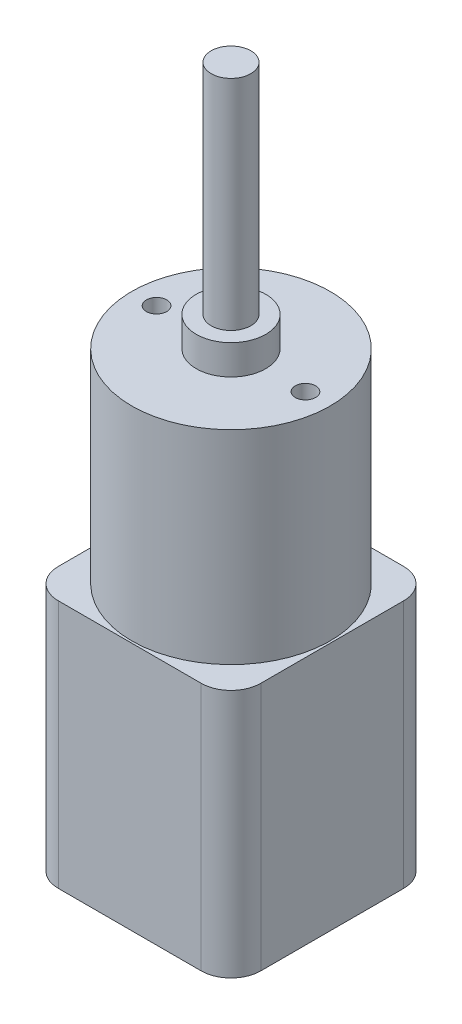
SolidWorks part; units mm, degrees
ref_plane "Front Plane" through (0, 0, 0) normal (0, 0, 1) x (1, 0, 0)
ref_plane "Top Plane" through (0, 0, 0) normal (0, 1, 0) x (1, 0, 0)
ref_plane "Right Plane" through (0, 0, 0) normal (1, 0, 0) x (0, 0, -1)
sketch "Sketch2" plane through (0, 0, 0) normal (0, 1, 0) x (1, 0, 0)
  line L1 (-10.2, -10.2) -> (10.2, -10.2)
  line L2 (-10.2, -10.2) -> (-10.2, 10.2)
  line L3 (-10.2, 10.2) -> (10.2, 10.2)
  line L4 (10.2, -10.2) -> (10.2, 10.2)
  line L5 (-10.2, -10.2) -> (10.2, 10.2) construction
  line L6 (-10.2, 10.2) -> (10.2, -10.2) construction
  point P0 (0, 0)
  dimension "D1" = 20.4
  dimension "D2" = 20.4
extrude "Boss-Extrude1" add sketch "Sketch2" along normal blind 25.1
sketch "Sketch3" plane through (0, 25.1, 0) normal (0, 1, 0) x (1, 0, 0)
  circle A0 centre (0, 0) radius 10
  dimension "D1" = 20
extrude "Boss-Extrude2" add sketch "Sketch3" along normal blind 20.5
sketch "Sketch4" plane through (0, 45.6, 0) normal (0, 1, 0) x (1, 0, 0)
  circle A0 centre (0, 0) radius 3.5
  dimension "D1" = 7
extrude "Boss-Extrude3" add sketch "Sketch4" along normal blind 3
sketch "Sketch5" plane through (0, 48.6, 0) normal (0, 1, 0) x (1, 0, 0)
  circle A0 centre (0, 0) radius 2
  dimension "D1" = 4
extrude "Boss-Extrude4" add sketch "Sketch5" along normal blind 22
sketch "Sketch6" plane through (0, 45.6, 0) normal (0, 1, 0) x (1, 0, 0)
  line L0 (0, 0) -> (-11.9549, 0) construction
  point P3 (-7.5, 0)
  point P4 (7.5, 0)
  dimension "D1" = 7.5
  dimension "D2" = 15
hole_wizard "M2.5 Tapped Hole1" positions "Sketch7" profile "Sketch8" tap size "M2.5" standard "ISO"
sketch "Sketch7" plane through (0, 45.6, 0) normal (0, 1, 0) x (1, 0, 0)
  point P0 (-7.5, 0)
  point P3 (7.5, 0)
sketch "Sketch8" plane through (-7.5, 45.6, 0) normal (1, 0, 0) x (0, 0, 1)
  line L0 (0, 0) -> (0, 5.6159)
  line L1 (0, 5.6159) -> (1.025, 5)
  line L2 (1.025, 5) -> (1.025, 0)
  line L5 (1.025, 0) -> (0, 0)
  line L10 (0, 5.6159) -> (-1.025, 5) construction
  line L11 (0, -6.35) -> (0, 107.95) construction
  dimension "Tap Drill Dia." = 2.05
  dimension "Tap Drill Depth" = 5
  dimension "Drill Angle" = 118
cosmetic thread "Hole Thread1" parameters "D1"=4.4, "D2"=2.5
cosmetic thread "Hole Thread2" parameters "D1"=4.4, "D2"=2.5
fillet "Fillet1" radius 3 4 edges at (10.2, 12.55, 10.2) (-10.2, 12.55, 10.2) (-10.2, 12.55, -10.2) (10.2, 12.55, -10.2)
